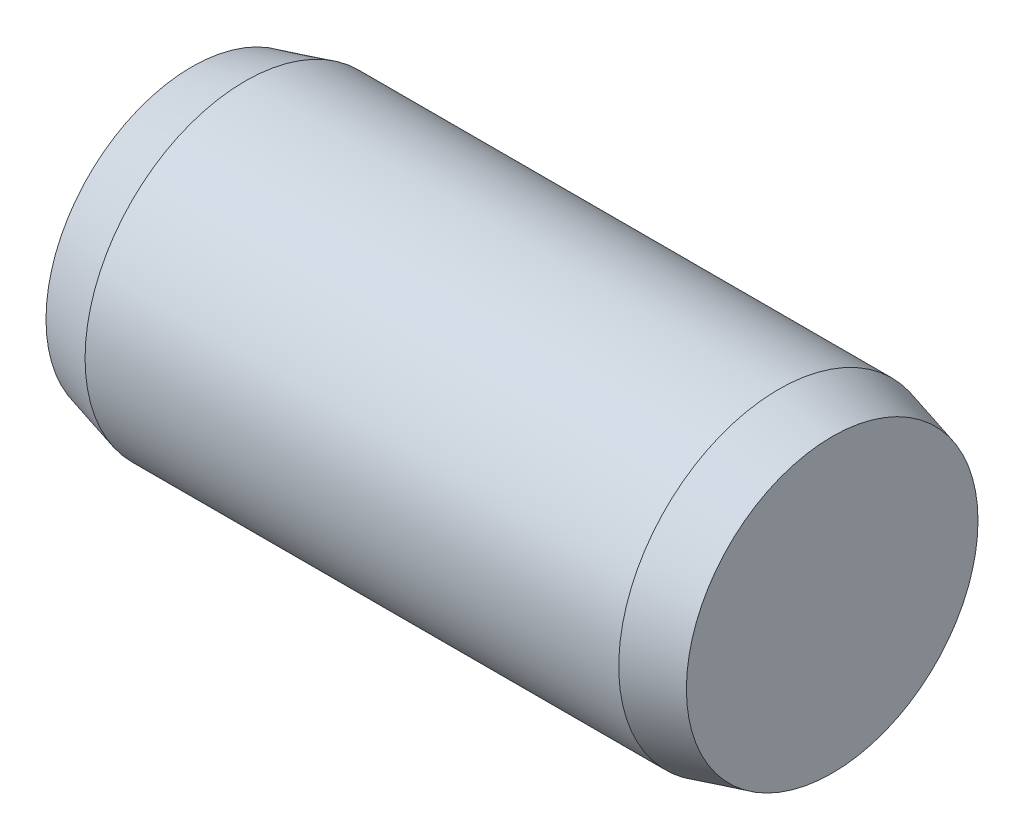
SolidWorks part; units mm, degrees
ref_plane "Front Plane" through (0, 0, 0) normal (0, 0, 1) x (1, 0, 0)
ref_plane "Top Plane" through (0, 0, 0) normal (0, 1, 0) x (1, 0, 0)
ref_plane "Right Plane" through (0, 0, 0) normal (1, 0, 0) x (0, 0, -1)
sketch "Sketch1" plane through (0, 0, 0) normal (0, 0, 1) x (1, 0, 0)
  line L0 (-2.5, 0) -> (2.5, 0) construction
  line L1 (2.5, 1.5) -> (2.5, -1.5) construction
  line L2 (-2.5, 1.5) -> (-2.5, -1.5) construction
  line L3 (3, 1.5) -> (3, -1.5) construction
  line L4 (-3, 1.5) -> (-3, -1.5) construction
  line L5 (-2.5, 0) -> (-3, 0) construction
  line L6 (2.5, 0) -> (3, 0) construction
  dimension "Dia" = 3
  dimension "C" = 0.5
  dimension "D1" = 0.5
  dimension "Length" = 6
sketch "Sketch2" plane through (0, 0, 0) normal (1, 0, 0) x (0, 0, -1)
  circle A0 centre (0, 0) radius 1.5
extrude "Extrude1" add sketch "Sketch2" against normal up to vertex (2.5 mm away) and the other way up to vertex (2.5 mm away) up to point (-2.5, 1.5, 0) other way up to point (2.5, 1.5, 0)
sketch "Sketch3" plane through (2.5, 0, 0) normal (1, 0, 0) x (0, 0, -1)
  circle A1 centre (0, 0) radius 1.5
  circle A2 centre (0, 0) radius 1.5
  dimension "D1" = 0
extrude "Extrude2" add sketch "Sketch3" along normal up to vertex (0.5 mm away) draft 15 up to point (3, 0, 0)
sketch "Sketch4" plane through (-2.5, 0, 0) normal (-1, 0, 0) x (0, 0, 1)
  circle A1 centre (0, 0) radius 1.5
  circle A2 centre (0, 0) radius 1.5
  dimension "D1" = 0
extrude "Extrude3" add sketch "Sketch4" along normal up to vertex (0.5 mm away) draft 15 up to point (-3, 0, 0)
equation "\"D1@Sketch1\" = \"C@Sketch1\""
